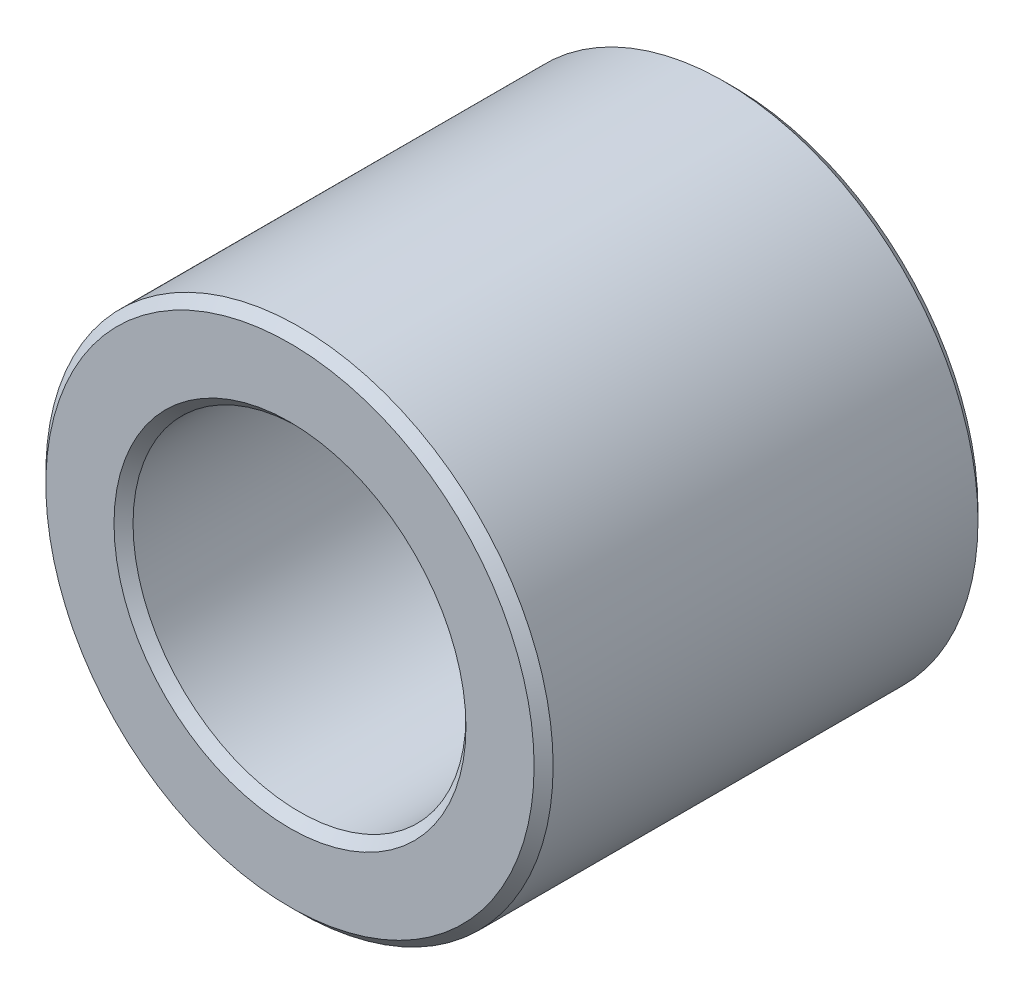
SolidWorks part; units mm, degrees
ref_plane "Front Plane" through (0, 0, 0) normal (0, 0, 1) x (1, 0, 0)
ref_plane "Top Plane" through (0, 0, 0) normal (0, 1, 0) x (1, 0, 0)
ref_plane "Right Plane" through (0, 0, 0) normal (1, 0, 0) x (0, 0, -1)
sketch "Sketch1" plane through (0, 0, 0) normal (0, 0, 1) x (1, 0, 0)
  circle A0 centre (0, 0) radius 8
  dimension "D1" = 16
extrude "Boss-Extrude1" add sketch "Sketch1" along normal blind 14 contours A0
sketch "Sketch2" plane through (0, 0, 0) normal (0, 0, 1) x (1, 0, 0)
  circle A0 centre (0, 0) radius 5.25
  dimension "D1" = 10.5
extrude "Cut-Extrude1" cut sketch "Sketch2" along normal blind 14
chamfer "Chamfer7" distance 0.3 angle 45 4 edges at (5.25, 0, 0) (8, 0, 0) (8, 0, 14) (5.25, 0, 14)
